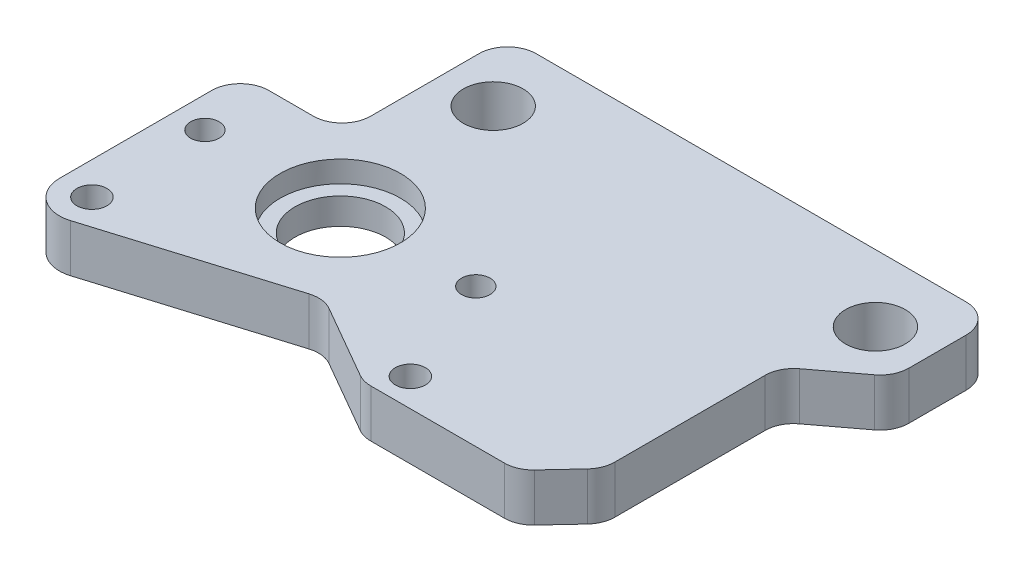
SolidWorks part; units mm, degrees
other "Markup1"
sketch "Sketch6" plane through (-23.3268, 0, -30.7975) normal (-0.0348, 0.9994, -0.0028) x (-0.9993, -0.0348, 0.0153)
sketch "Sketch7" plane through (-23.3268, 0, -30.7975) normal (-0.0348, 0.9994, -0.0028) x (-0.9993, -0.0348, 0.0153)
sketch "Sketch8" plane through (-23.3268, 0, -30.7975) normal (-0.0348, 0.9994, -0.0028) x (-0.9993, -0.0348, 0.0153)
sketch "Sketch10" plane through (-23.3268, 0, -30.7975) normal (-0.0348, 0.9994, -0.0028) x (-0.9993, -0.0348, 0.0153)
sketch "Sketch13" plane through (-23.3268, 0, -30.7975) normal (-0.0348, 0.9994, -0.0028) x (-0.9993, -0.0348, 0.0153)
sketch "Sketch15" plane through (-23.3268, 0, -30.7975) normal (-0.0348, 0.9994, -0.0028) x (-0.9993, -0.0348, 0.0153)
sketch "Sketch16" [suppressed] plane through (-23.3268, 0, -30.7975) normal (-0.0348, 0.9994, -0.0028) x (-0.9993, -0.0348, 0.0153)
sketch "Sketch17" plane through (-23.3268, 0, -30.7975) normal (-0.0348, 0.9994, -0.0028) x (-0.9993, -0.0348, 0.0153)
sketch "Sketch18" plane through (-23.3268, 0, -30.7975) normal (-0.0348, 0.9994, -0.0028) x (-0.9993, -0.0348, 0.0153)
sketch "Sketch19" [suppressed] plane through (-23.3268, 0, -30.7975) normal (-0.0348, 0.9994, -0.0028) x (-0.9993, -0.0348, 0.0153)
sketch "Sketch21" plane through (-23.3268, 0, -30.7975) normal (-0.0348, 0.9994, -0.0028) x (-0.9993, -0.0348, 0.0153)
sketch "Sketch23" plane through (-23.3268, 0, -30.7975) normal (-0.0348, 0.9994, -0.0028) x (-0.9993, -0.0348, 0.0153)
sketch "Sketch24" plane through (-23.3268, 0, -30.7975) normal (-0.0348, 0.9994, -0.0028) x (-0.9993, -0.0348, 0.0153)
sketch "Sketch25" plane through (-23.3268, 0, -30.7975) normal (-0.0348, 0.9994, -0.0028) x (-0.9993, -0.0348, 0.0153)
sketch "Sketch26" [suppressed] plane through (-23.3268, 0, -30.7975) normal (-0.0348, 0.9994, -0.0028) x (-0.9993, -0.0348, 0.0153)
sketch "Sketch27" plane through (-23.3268, 0, -30.7975) normal (-0.0348, 0.9994, -0.0028) x (-0.9993, -0.0348, 0.0153)
sketch "Sketch28" plane through (-23.3268, 0, -30.7975) normal (-0.0348, 0.9994, -0.0028) x (-0.9993, -0.0348, 0.0153)
sketch "Sketch29" plane through (-23.3268, 0, -30.7975) normal (-0.0348, 0.9994, -0.0028) x (-0.9993, -0.0348, 0.0153)
sketch "Sketch30" plane through (-23.3268, 0, -30.7975) normal (-0.0348, 0.9994, -0.0028) x (-0.9993, -0.0348, 0.0153)
sketch "Sketch32" plane through (-23.3268, 0, -30.7975) normal (-0.0348, 0.9994, -0.0028) x (-0.9993, -0.0348, 0.0153)
sketch "Sketch34" [suppressed] plane through (-23.3268, 0, -30.7975) normal (-0.0348, 0.9994, -0.0028) x (-0.9993, -0.0348, 0.0153)
sketch "Sketch35" [suppressed] plane through (-23.3268, 0, -30.7975) normal (-0.0348, 0.9994, -0.0028) x (-0.9993, -0.0348, 0.0153)
sketch "Sketch36" [suppressed] plane through (-23.3268, 0, -30.7975) normal (-0.0348, 0.9994, -0.0028) x (-0.9993, -0.0348, 0.0153)
sketch "Sketch37" plane through (-23.3268, 0, -30.7975) normal (-0.0348, 0.9994, -0.0028) x (-0.9993, -0.0348, 0.0153)
sketch "Sketch38" plane through (-23.3268, 0, -30.7975) normal (-0.0348, 0.9994, -0.0028) x (-0.9993, -0.0348, 0.0153)
sketch "Sketch39" [suppressed] plane through (-23.3268, 0, -30.7975) normal (-0.0348, 0.9994, -0.0028) x (-0.9993, -0.0348, 0.0153)
sketch "Sketch40" plane through (-23.3268, 0, -30.7975) normal (-0.0348, 0.9994, -0.0028) x (-0.9993, -0.0348, 0.0153)
sketch "Sketch41" plane through (-23.3268, 0, -30.7975) normal (-0.0348, 0.9994, -0.0028) x (-0.9993, -0.0348, 0.0153)
sketch "Sketch42" plane through (-23.3268, 0, -30.7975) normal (-0.0348, 0.9994, -0.0028) x (-0.9993, -0.0348, 0.0153)
sketch "Sketch43" plane through (-23.3268, 0, -30.7975) normal (-0.0348, 0.9994, -0.0028) x (-0.9993, -0.0348, 0.0153)
sketch "Sketch44" plane through (-23.3268, 0, -30.7975) normal (-0.0348, 0.9994, -0.0028) x (-0.9993, -0.0348, 0.0153)
sketch "Sketch45" plane through (-23.3268, 0, -30.7975) normal (-0.0348, 0.9994, -0.0028) x (-0.9993, -0.0348, 0.0153)
sketch "Sketch46" plane through (-23.3268, 0, -30.7975) normal (-0.0348, 0.9994, -0.0028) x (-0.9993, -0.0348, 0.0153)
sketch "Sketch47" plane through (-23.3268, 0, -30.7975) normal (-0.0348, 0.9994, -0.0028) x (-0.9993, -0.0348, 0.0153)
sketch "Sketch48" plane through (-23.3268, 0, -30.7975) normal (-0.0348, 0.9994, -0.0028) x (-0.9993, -0.0348, 0.0153)
sketch "Sketch49" plane through (-23.3268, 0, -30.7975) normal (-0.0348, 0.9994, -0.0028) x (-0.9993, -0.0348, 0.0153)
sketch "Sketch50" plane through (-23.3268, 0, -30.7975) normal (-0.0348, 0.9994, -0.0028) x (-0.9993, -0.0348, 0.0153)
material "6061-T6 (SS)"
ref_plane "X-Y Datum" through (0, 0, 0) normal (0, 0, 1) x (1, 0, 0)
ref_plane "X-Z Datum" through (0, 0, 0) normal (0, 1, 0) x (1, 0, 0)
ref_plane "Y-Z Datum" through (0, 0, 0) normal (1, 0, 0) x (0, 0, -1)
other "Graphic1"
other "Graphic (Closed) -1"
other "Graphic (Closed) -2"
sketch "Sketch2" plane through (0, 0, 0) normal (0, 1, 0) x (1, 0, 0)
  line L0 (48.6426, -18.7325) -> (-23.0162, -18.7325)
  line L1 (24.0125, -14.7036) -> (25.7865, -13.7801) construction
  line L2 (0, 0) -> (105.5557, -202.7707) construction
  line L3 (11.142, -21.4036) -> (-3.5026, -29.027) construction
  line L4 (0, 0) -> (0, -121.3797) construction
  line L5 (-3.5026, -29.027) -> (90.9112, -210.3941) construction
  line L6 (90.9112, -210.3941) -> (105.5557, -202.7707) construction
  line L7 (11.142, -21.4036) -> (24.0125, -14.7036) construction
  line L11 (-12.7, 30.7975) -> (57.15, 30.7975)
  line L12 (57.15, 13.0175) -> (57.15, 30.7975)
  line L13 (57.15, 13.0175) -> (-12.7, 13.0175) construction
  line L15 (44.7685, -18.0975) -> (44.7685, -11.3157) construction
  line L16 (44.7685, -18.0975) -> (34.8625, -18.0975) construction
  line L18 (44.7685, 9.8425) -> (34.8625, 9.8425) construction
  line L20 (44.7685, -11.3157) -> (49.8485, -11.3157) construction
  line L21 (49.8485, -11.3157) -> (49.8485, 3.0607) construction
  line L22 (49.8485, 3.0607) -> (44.7685, 3.0607) construction
  line L23 (44.7685, 3.0607) -> (44.7685, 9.8425) construction
  line L24 (34.8625, -18.0975) -> (34.8625, 9.8425) construction
  line L25 (48.6426, -18.7325) -> (57.15, 13.0175)
  line L26 (-12.7, 30.7975) -> (-12.7, 13.0175)
  line L28 (-12.5603, 0) -> (-16.51, -40.5272) construction
  line L30 (-23.0162, -18.7325) -> (-12.7, 13.0175)
  circle A0 centre (0, 0) radius 3.175
  circle A1 centre (24.0125, -14.7036) radius 2
  circle A2 centre (-1.5875, 21.9075) radius 3.9688
  circle A3 centre (49.2125, 21.9075) radius 3.9687
  circle A4 centre (39.8485, -4.1275) radius 5.1
  circle A5 centre (24.0125, -14.7036) radius 3.175 construction
  circle A6 centre (39.8485, -14.6275) radius 1.6
  circle A7 centre (39.8485, 6.3725) radius 1.6
  circle A8 centre (-17.2047, -14.9225) radius 3.175 construction
  circle A9 centre (-17.2047, -14.9225) radius 2
  point P9 (11.142, -21.4036)
  point P30 (49.8485, -4.1275)
  point P31 (34.8625, -4.1275)
  dimension "D1" = 6.35
  dimension "D8" = 4
  dimension "D10" = 7.9375
  dimension "D11" = 7.9375
  dimension "D16" = 27.94
  dimension "D23" = 10.2
  dimension "D20" = 6.35
  dimension "D30" = 3.2
  dimension "D32" = 3.2
  dimension "D34" = 6.35
  dimension "D35" = 4
  dimension "D3" = 13.0175
  dimension "D4" = 16.51
  dimension "D5" = 228.6
  dimension "D6" = 24.13
  dimension "D7" = 27.5
  dimension "D9" = 16.51
  dimension "D12" = 8.89
  dimension "D13" = 69.85
  dimension "D14" = 7.9375
  dimension "D15" = 31.75
  dimension "D17" = 17.78
  dimension "D18" = 3.175
  dimension "D19" = 14.986
  dimension "D21" = 5.08
  dimension "D22" = 14.3764
  dimension "D24" = 10
  dimension "D25" = 36.83
  dimension "D26" = 50.8
  dimension "D27" = 165
  dimension "D28" = 12.7
  dimension "D29" = 17.3015
  dimension "D31" = 10.5
  dimension "D33" = 10.5
  dimension "D36" = 162
extrude "Boss-Extrude1" [suppressed] add sketch "Sketch2" against normal blind 6.35
ref_point "Point1" [suppressed]
sketch "Sketch3" [suppressed] plane through (0, 0, 0) normal (0, 1, 0) x (1, 0, 0)
  line L0 (39.9681, 6.3725) -> (39.9681, -4.1275) construction
  line L1 (57.2697, 12.9663) -> (-12.5803, 12.9663) construction
  line L5 (39.9681, -4.1275) -> (39.9681, -14.6275) construction
  line L6 (42.0297, -18.7325) -> (20.4164, -18.7325)
  line L7 (57.2697, 12.9663) -> (57.2697, 30.7975)
  line L8 (57.2697, 30.7975) -> (-12.5803, 30.7975)
  line L9 (-12.5803, 30.7975) -> (-12.5803, 12.9663)
  line L10 (40.938, 24.6176) -> (16.9472, 10.7666)
  line L11 (13.3942, 11.8528) -> (6.9035, 25.1608)
  line L12 (8.045, 26.9875) -> (40.303, 26.9875)
  line L13 (57.2697, 12.9663) -> (48.3797, 12.9663)
  line L14 (48.3797, 12.9663) -> (48.3797, -12.3825)
  line L16 (-23.0162, -18.7325) -> (48.6426, -18.7325) construction
  line L18 (16.6064, -14.8627) -> (10.2787, -14.8627)
  line L21 (-8.965, -15.5427) -> (-15.106, -18.7325)
  line L24 (-21.1701, -13.6017) -> (-12.5803, 12.9663)
  line L29 (17.8764, -16.1925) -> (17.8764, -16.1327)
  circle A0 centre (0.1197, 0) radius 3.175
  circle A1 centre (-1.4678, 21.9075) radius 3.9688
  circle A2 centre (49.3322, 21.9075) radius 3.9687
  circle A3 centre (39.9681, -4.1275) radius 5.1
  circle A4 centre (39.9681, -14.6275) radius 1.6
  circle A5 centre (39.9681, 6.3725) radius 1.6
  circle A6 centre (24.1322, -14.7036) radius 2
  circle A7 centre (-17.085, -14.9225) radius 2
  arc A8 (13.3942, 11.8528) -> (16.9472, 10.7666) centre (15.6772, 12.9663) ccw
  arc A9 (8.045, 26.9875) -> (6.9035, 25.1608) centre (8.045, 25.7175) ccw
  arc A10 (40.938, 24.6176) -> (40.303, 26.9875) centre (40.303, 25.7175) ccw
  arc A11 (10.2787, -14.8627) -> (-8.965, -15.5427) centre (0.1197, 0) cw
  arc A12 (-15.106, -18.7325) -> (-21.1701, -13.6017) centre (-17.085, -14.9225) cw
  arc A13 (42.0297, -18.7325) -> (48.3797, -12.3825) centre (42.0297, -12.3825) ccw
  arc A14 (20.4164, -18.7325) -> (17.8764, -16.1925) centre (20.4164, -16.1925) cw
  arc A15 (16.6064, -14.8627) -> (17.8764, -16.1327) centre (16.6064, -16.1327) cw
  dimension "D1" = 6.35
  dimension "D4" = 7.9375
  dimension "D9" = 10.2
  dimension "D10" = 3.2
  dimension "D11" = 4
  dimension "D21" = 2.54
  dimension "D22" = 1.27
  dimension "D3" = 6.35
  dimension "D28" = 2.54
  dimension "D29" = 1.27
  dimension "D2" = 7.9375
  dimension "D5" = 50.8
  dimension "D6" = 21.9075
  dimension "D7" = 1.5875
  dimension "D8" = 8.89
  dimension "D12" = 10.5
  dimension "D13" = 17.2047
  dimension "D14" = 24.0125
  dimension "D15" = 14.7036
  dimension "D16" = 39.8485
  dimension "D17" = 4.1275
  dimension "D18" = 14.9225
  dimension "D19" = 69.85
  dimension "D20" = 3.81
  dimension "D23" = 30
  dimension "D24" = 64
  dimension "D25" = 32.258
  dimension "D26" = 15.5575
  dimension "D27" = 25.3488
  dimension "D30" = 8.89
sketch "Sketch4" plane through (0, 0, 0) normal (0, 1, 0) x (1, 0, 0)
  line L0 (39.8485, 6.3725) -> (39.8485, -4.1275) construction
  line L1 (56.1975, 13.0175) -> (-8.5725, 13.0175) construction
  line L2 (39.8485, -4.1275) -> (39.8485, -14.6275) construction
  line L3 (40.2577, -18.4375) -> (22.4839, -18.4375)
  line L5 (52.3875, 30.7975) -> (-4.7625, 30.7975)
  line L6 (-8.5725, 26.9875) -> (-8.5725, 12.6075)
  line L40 (47.4685, 8.9851) -> (47.4685, -10.9806)
  line L41 (46.4449, -13.579) -> (43.0442, -17.2259)
  line L43 (48.9856, 12.0279) -> (54.6804, 16.3193)
  line L44 (56.1975, 19.3621) -> (56.1975, 26.9875)
  line L50 (-17.78, -15.24) -> (0, 0) construction
  line L58 (20.5837, -17.9298) -> (10.7795, -12.2883)
  line L59 (0, 0) -> (0, 5.6144) construction
  line L60 (7.7656, -11.947) -> (-16.5178, -19.3694)
  line L61 (-22.098, -15.24) -> (-22.098, 4.9875)
  line L62 (-18.288, 8.7975) -> (-12.3825, 8.7975)
  circle A0 centre (0, 0) radius 8
  circle A1 centre (-1.5875, 21.9075) radius 3.9688
  circle A2 centre (49.2125, 21.9075) radius 3.9687
  circle A6 centre (24.0125, -14.7036) radius 2
  circle A7 centre (-17.78, -15.24) radius 2
  arc A12 (-16.5178, -19.3694) -> (-22.098, -15.24) centre (-17.78, -15.24) cw
  arc A19 (-8.5725, 26.9875) -> (-4.7625, 30.7975) centre (-4.7625, 26.9875) cw
  arc A20 (52.3875, 30.7975) -> (56.1975, 26.9875) centre (52.3875, 26.9875) cw
  circle A33 centre (24.0125, -14.7036) radius 3.5 construction
  arc A45 (56.1975, 19.3621) -> (54.6804, 16.3193) centre (52.3875, 19.3621) cw
  arc A46 (47.4685, 8.9851) -> (48.9856, 12.0279) centre (51.2785, 8.9851) cw
  arc A47 (47.4685, -10.9806) -> (46.4449, -13.579) centre (43.6585, -10.9806) cw
  arc A48 (43.0442, -17.2259) -> (40.2577, -18.4375) centre (40.2577, -14.6275) cw
  arc A51 (-22.098, 4.9875) -> (-18.288, 8.7975) centre (-18.288, 4.9875) cw
  arc A52 (-12.3825, 8.7975) -> (-8.5725, 12.6075) centre (-12.3825, 12.6075) ccw
  arc A53 (22.4839, -18.4375) -> (20.5837, -17.9298) centre (22.4839, -14.6275) cw
  arc A54 (7.7656, -11.947) -> (10.7795, -12.2883) centre (8.8793, -15.5906) cw
  circle A55 centre (0, 0) radius 18 construction
  circle A57 centre (18, 0) radius 1.8986
  circle A58 centre (-18, 0) radius 1.8986
  point P30 (21.466, -18.4375)
  point P36 (9.3466, -11.4637)
  point P58 (-8.5725, 30.7975)
  point P77 (56.1975, 17.4625)
  point P84 (41.9143, -18.4375)
  dimension "D1" = 16
  dimension "D2" = 7.9375
  dimension "D7" = 22
  dimension "D8" = 4
  dimension "D19" = 3.81
  dimension "D20" = 6.9738
  dimension "D25" = 3.81
  dimension "D26" = 7
  dimension "D27" = 25.8644
  dimension "D31" = 3.7973
  dimension "D33" = 4.318
  dimension "D23" = 3.81
  dimension "D45" = 3.81
  dimension "D18" = 3.81
  dimension "D29" = 3.81
  dimension "D30" = 36
  dimension "D3" = 50.8
  dimension "D4" = 21.9075
  dimension "D5" = 1.5875
  dimension "D9" = 10.5
  dimension "D10" = 24.0125
  dimension "D11" = 14.7036
  dimension "D12" = 39.8485
  dimension "D13" = 4.1275
  dimension "D14" = 15.24
  dimension "D15" = 17.78
  dimension "D16" = 6.985
  dimension "D17" = 8.89
  dimension "D21" = 17.78
  dimension "D22" = 12.1194
  dimension "D24" = 7.62
  dimension "D28" = 4.9865
  dimension "D36" = 9.525
  dimension "D40" = 127
  dimension "D43" = 137
  dimension "D60" = 6.985
extrude "Boss-Extrude2" add sketch "Sketch4" against normal blind 6.35
ref_point "Point2"
ref_point "Point3"
ref_point "Point4"
sketch "Sketch31" plane through (0, -6.35, 0) normal (0, -1, 0) x (1, 0, 0)
  circle A0 centre (0, 0) radius 6.025
  circle A1 centre (0, 0) radius 8
  dimension "D1" = 12.05
  dimension "D2" = 16
extrude "Boss-Extrude5" add sketch "Sketch31" against normal blind 3.5
sketch "Sketch33" [suppressed] plane through (0, 0, 0) normal (0, 1, 0) x (1, 0, 0)
  circle A0 centre (0, 0) radius 8
  circle A1 centre (0, 0) radius 6.025
  dimension "D1" = 12.05
  dimension "D2" = 16
extrude "Boss-Extrude6" [suppressed] add sketch "Sketch33" against normal blind 3.5
